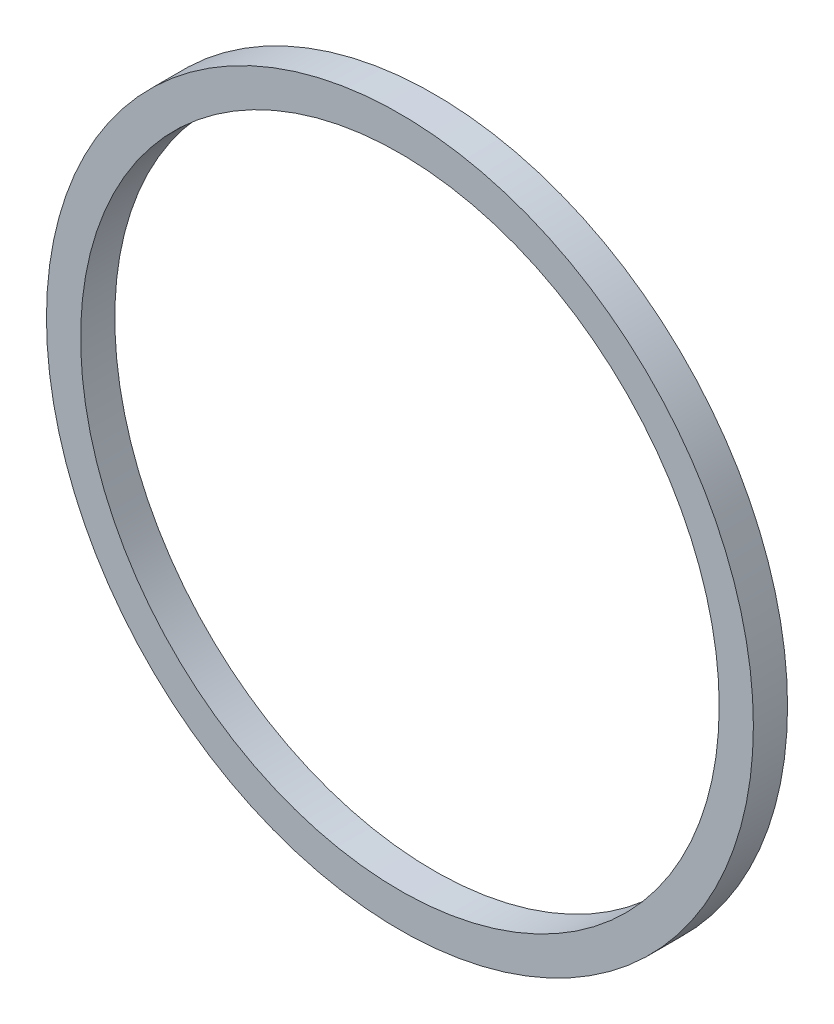
SolidWorks part; units mm, degrees
ref_plane "Front Plane" through (0, 0, 0) normal (0, 0, 1) x (1, 0, 0)
ref_plane "Top Plane" through (0, 0, 0) normal (0, 1, 0) x (1, 0, 0)
ref_plane "Right Plane" through (0, 0, 0) normal (1, 0, 0) x (0, 0, -1)
sketch "Sketch1" plane through (0, 0, 0) normal (0, 0, 1) x (1, 0, 0)
  line L0 (-27.0637, 0) -> (27.0637, 0) construction
  line L1 (-24.4475, 0) -> (24.4475, 0) construction
  line L2 (-19.1369, 19.1369) -> (19.1369, -19.1369) construction
  point P3 (24.4475, 0)
  point P4 (0, 0)
  point P8 (0, 0)
  point P9 (0, 0)
  point P10 (-27.0637, 0)
  point P11 (-24.4475, 0)
  point P14 (0, 0)
  point P15 (19.1369, -19.1369)
  point P16 (27.0637, 0)
  dimension "Actual OD" = 54.1274
  dimension "Actual ID" = 48.895
  dimension "Actual Width" = 2.6162
  dimension "D1" = 45
sketch "Sketch2" plane through (0, 0, 0) normal (0, 1, 0) x (1, 0, 0)
  line L1 (-25.7556, 1.3081) -> (-25.7556, -1.3081) construction
  line L2 (0, -1.3081) -> (0, 1.3081) construction
  line L3 (-27.0637, 0) -> (27.0637, 0) construction
  line L4 (-27.0637, -1.3081) -> (-24.4475, -1.3081)
  line L5 (-27.0637, -1.3081) -> (-27.0637, 1.3081)
  line L6 (-27.0637, 1.3081) -> (-24.4475, 1.3081)
  line L7 (-24.4475, -1.3081) -> (-24.4475, 1.3081)
  line L9 (-27.0637, 0) -> (-24.4475, 0) construction
  point P0 (-25.7556, 0)
  point P12 (0, 0)
revolve "Revolve1" add sketch "Sketch2" angle 360 about L2
sketch "Sketch3" plane through (0, 0, 0) normal (1, 0, 0) x (0, 0, -1)
  line L0 (-1.3081, 0) -> (1.3081, 0) construction
  line L1 (-1.3081, -18.3356) -> (-1.3081, 18.3356) construction
  point P4 (0, 0)
  point P7 (-1.3081, 0)
  point P9 (-1.3081, -18.3356)
  dimension "D1" = 2.6162
  dimension "D2" = 36.6713
equation "\"D1@Sketch3\"=\"Actual Width@Sketch1\""
equation "\"D2@Sketch3\"=\"Actual ID@Sketch1\"*.75"
